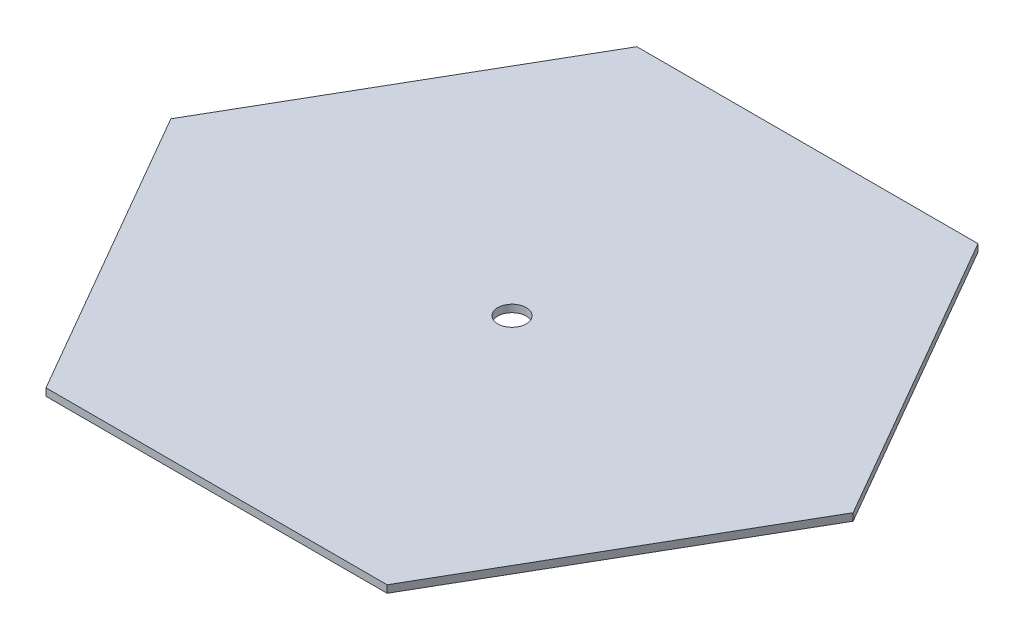
SolidWorks part; units mm, degrees
ref_plane "Front Plane" through (0, 0, 0) normal (0, 0, 1) x (1, 0, 0)
ref_plane "Top Plane" through (0, 0, 0) normal (0, 1, 0) x (1, 0, 0)
ref_plane "Right Plane" through (0, 0, 0) normal (1, 0, 0) x (0, 0, -1)
sketch "Sketch1" plane through (0, 0, 0) normal (0, 1, 0) x (1, 0, 0)
  line L1 (69.282, 120) -> (-69.282, 120)
  line L2 (-69.282, 120) -> (-138.5641, 0)
  line L3 (-138.5641, 0) -> (-69.282, -120)
  line L4 (-69.282, -120) -> (69.282, -120)
  line L5 (69.282, -120) -> (138.5641, 0)
  line L6 (138.5641, 0) -> (69.282, 120)
  circle A0 centre (0, 0) radius 120 construction
  dimension "D1" = 240
extrude "Boss-Extrude1" add sketch "Sketch1" along normal blind 3
sketch "Sketch2" plane through (0, 0, 0) normal (0, 1, 0) x (1, 0, 0)
  line L0 (0, 0) -> (103.923, 60) construction
  line L1 (138.5641, 0) -> (69.282, 120) construction
  line L2 (75.5513, 30.8586) -> (53.0513, -8.1125) construction
  line L3 (66.5368, -29.7548) -> (27.5657, -7.2548) construction
  line L6 (33.5657, 3.1375) -> (72.5368, -19.3625) construction
  line L7 (72.5368, -19.3625) -> (95.0368, 19.6086) construction
  line L8 (95.0368, 19.6086) -> (56.0657, 42.1086) construction
  line L9 (56.0657, 42.1086) -> (33.5657, 3.1375) construction
  line L10 (-14.0657, -30.6375) -> (-53.0368, -53.1375) construction
  line L11 (8.4343, -69.6086) -> (-14.0657, -30.6375) construction
  line L12 (-30.5368, -92.1086) -> (8.4343, -69.6086) construction
  line L13 (-53.0368, -53.1375) -> (-30.5368, -92.1086) construction
  line L14 (-19.5, 27.5) -> (-19.5, 72.5) construction
  line L15 (-64.5, 27.5) -> (-19.5, 27.5) construction
  line L16 (-64.5, 72.5) -> (-64.5, 27.5) construction
  line L17 (-19.5, 72.5) -> (-64.5, 72.5) construction
  line L19 (53.0513, -8.1125) -> (43.3013, -25) construction
  line L21 (103.923, -60) -> (0, 0) construction
  line L22 (69.282, -120) -> (138.5641, 0) construction
  point P9 (47.0513, -18.5048)
  point P18 (33.5657, 3.1375)
  point P19 (56.0657, 42.1086)
  point P20 (95.0368, 19.6086)
  point P21 (72.5368, -19.3625)
  point P31 (0, 0)
  dimension "D1" = 45
  dimension "D2" = 45
  dimension "D4" = 7.5
  dimension "D5" = 12
  dimension "D6" = 50
  dimension "D3" = 3
sketch "Sketch5" plane through (0, 3, 0) normal (0, 1, 0) x (1, 0, 0)
  circle A0 centre (0, 0) radius 5.7532
extrude "Cut-Extrude1" cut sketch "Sketch5" against normal through all
